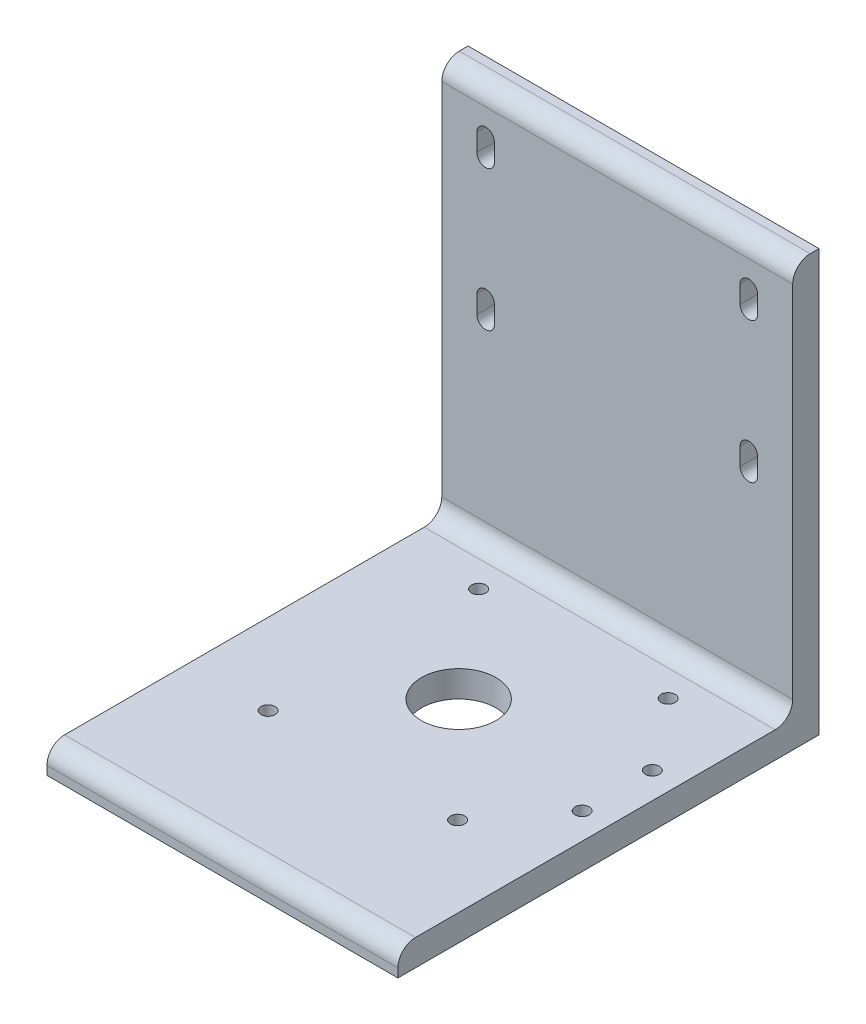
SolidWorks part; units mm, degrees
ref_plane "Front Plane" through (0, 0, 0) normal (0, 0, 1) x (1, 0, 0)
ref_plane "Top Plane" through (0, 0, 0) normal (0, 1, 0) x (1, 0, 0)
ref_plane "Right Plane" through (0, 0, 0) normal (1, 0, 0) x (0, 0, -1)
sketch "Sketch1" plane through (0, 0, 0) normal (1, 0, 0) x (0, 0, -1)
  line L0 (0, 0) -> (0, 152.4)
  line L1 (0, 152.4) -> (-9.525, 152.4)
  line L2 (-9.525, 152.4) -> (-9.525, 9.525)
  line L3 (-9.525, 9.525) -> (-152.4, 9.525)
  line L4 (-152.4, 9.525) -> (-152.4, 0)
  line L5 (-152.4, 0) -> (0, 0)
  dimension "D1" = 9.525
  dimension "D2" = 152.4
extrude "6\" x 6\" angle bar extrusion" add sketch "Sketch1" along normal mid plane 127
fillet "extrusion fillets" radius 6.35 3 edges at (0, 9.525, 152.4) (0, 152.4, 9.525) (0, 9.525, 9.525)
hole_wizard "#10 Clearance Hole - router" positions "Sketch4" profile "Sketch3" hole size "#10" standard "ANSI Inch" end condition up to next
sketch "Sketch4" plane through (0, 9.525, 0) normal (0, 1, 0) x (1, 0, 0)
  line L0 (0, 0) -> (0, -25.4) construction
  line L3 (-34.29, -25.4) -> (34.29, -25.4) construction
  line L4 (-34.29, -25.4) -> (-34.29, -101.6) construction
  line L5 (-34.29, -101.6) -> (34.29, -101.6) construction
  line L6 (34.29, -25.4) -> (34.29, -101.6) construction
  point P6 (-34.29, -25.4)
  point P7 (34.29, -101.6)
  point P18 (-34.29, -101.6)
  point P19 (34.29, -25.4)
  dimension "D1" = 76.2
  dimension "D2" = 68.58
  dimension "D3" = 25.4
sketch "Sketch3" plane through (-34.29, 9.525, 25.4) normal (1, 0, 0) x (0, 0, 1)
  line L0 (0, 0) -> (0, 9.525)
  line L1 (0, 9.525) -> (2.5527, 9.525)
  line L2 (2.5527, 9.525) -> (2.5527, 0)
  line L5 (2.5527, 0) -> (0, 0)
  line L11 (0, -6.35) -> (0, 107.95) construction
  dimension "Thru Hole Dia." = 5.1054
  dimension "Thru Hole Depth" = 9.525
sketch "Sketch7" plane through (0, 9.525, 0) normal (0, 1, 0) x (1, 0, 0)
  circle A0 centre (-3.4036, -63.5) radius 13.4938
  circle A1 centre (-34.29, -25.4) radius 2.5527 construction
  dimension "D1" = 26.9875
  dimension "D3" = 30.8864
  dimension "D2" = 38.1
extrude "1\" OD bit access hole" cut sketch "Sketch7" against normal through all
hole_wizard "Tapped Hole for #10-32 Helicoil1" positions "Sketch13" profile "Sketch12" tap size "#10-32" standard "Helicoil® Inch"
sketch "Sketch13" plane through (0, 0, 0) normal (0, -1, 0) x (-1, 0, 0)
  line L0 (-53.975, 0) -> (-53.975, -82.8685) construction
  line L1 (-63.5, 0) -> (63.5, 0) construction
  line L3 (-63.5, -152.4) -> (-63.5, 0) construction
  point P8 (-53.975, -50.8)
  point P10 (-53.975, -76.2)
  dimension "D1" = 9.525
  dimension "D2" = 25.4
  dimension "D3" = 50.8
sketch "Sketch12" plane through (53.975, 0, 50.8) normal (1, 0, 0) x (0, 0, -1)
  line L0 (0, 0) -> (0, 11.0578)
  line L1 (0, 11.0578) -> (2.5527, 9.524)
  line L2 (2.5527, 9.524) -> (2.5527, 0)
  line L5 (2.5527, 0) -> (0, 0)
  line L10 (0, 11.0578) -> (-2.5527, 9.524) construction
  line L11 (0, -6.35) -> (0, 107.95) construction
  dimension "Tap Drill Dia." = 5.1054
  dimension "Tap Drill Depth" = 9.524
  dimension "Drill Angle" = 118
sketch "Sketch14" plane through (0, 0, 0) normal (0, 0, -1) x (-1, 0, 0)
  line L0 (0, 82.55) -> (0, 0) construction
  line L1 (-47.625, 133.35) -> (47.625, 133.35) construction
  line L2 (-47.625, 133.35) -> (-47.625, 82.55) construction
  line L3 (-47.625, 82.55) -> (47.625, 82.55) construction
  line L4 (47.625, 133.35) -> (47.625, 82.55) construction
  line L5 (-47.625, 136.525) -> (-47.625, 130.175) construction
  line L6 (-44.45, 136.525) -> (-44.45, 130.175)
  line L7 (-50.8, 136.525) -> (-50.8, 130.175)
  line L8 (-47.625, 85.725) -> (-47.625, 79.375) construction
  line L9 (-44.45, 85.725) -> (-44.45, 79.375)
  line L10 (-50.8, 85.725) -> (-50.8, 79.375)
  line L11 (47.625, 85.725) -> (47.625, 79.375) construction
  line L12 (50.8, 85.725) -> (50.8, 79.375)
  line L13 (44.45, 85.725) -> (44.45, 79.375)
  line L14 (47.625, 136.525) -> (47.625, 130.175) construction
  line L15 (50.8, 136.525) -> (50.8, 130.175)
  line L16 (44.45, 136.525) -> (44.45, 130.175)
  arc A0 (-44.45, 136.525) -> (-50.8, 136.525) centre (-47.625, 136.525) ccw
  arc A1 (-50.8, 130.175) -> (-44.45, 130.175) centre (-47.625, 130.175) ccw
  arc A2 (-44.45, 85.725) -> (-50.8, 85.725) centre (-47.625, 85.725) ccw
  arc A3 (-50.8, 79.375) -> (-44.45, 79.375) centre (-47.625, 79.375) ccw
  arc A4 (50.8, 85.725) -> (44.45, 85.725) centre (47.625, 85.725) ccw
  arc A5 (44.45, 79.375) -> (50.8, 79.375) centre (47.625, 79.375) ccw
  arc A6 (50.8, 136.525) -> (44.45, 136.525) centre (47.625, 136.525) ccw
  arc A7 (44.45, 130.175) -> (50.8, 130.175) centre (47.625, 130.175) ccw
  point P9 (-47.625, 133.35)
  point P15 (-47.625, 82.55)
  point P22 (47.625, 82.55)
  point P29 (47.625, 133.35)
  dimension "D5" = 3.175
  dimension "D1" = 82.55
  dimension "D2" = 95.25
  dimension "D3" = 50.8
  dimension "D4" = 6.35
extrude "mounting slots" cut sketch "Sketch14" against normal up to next
ref_plane "Plane1 - bottom" through (0, 82.55, 0) normal (0, -1, 0) x (-1, 0, 0)
ref_plane "Plane2 - top" through (0, 133.35, 0) normal (0, -1, 0) x (-1, 0, 0)
